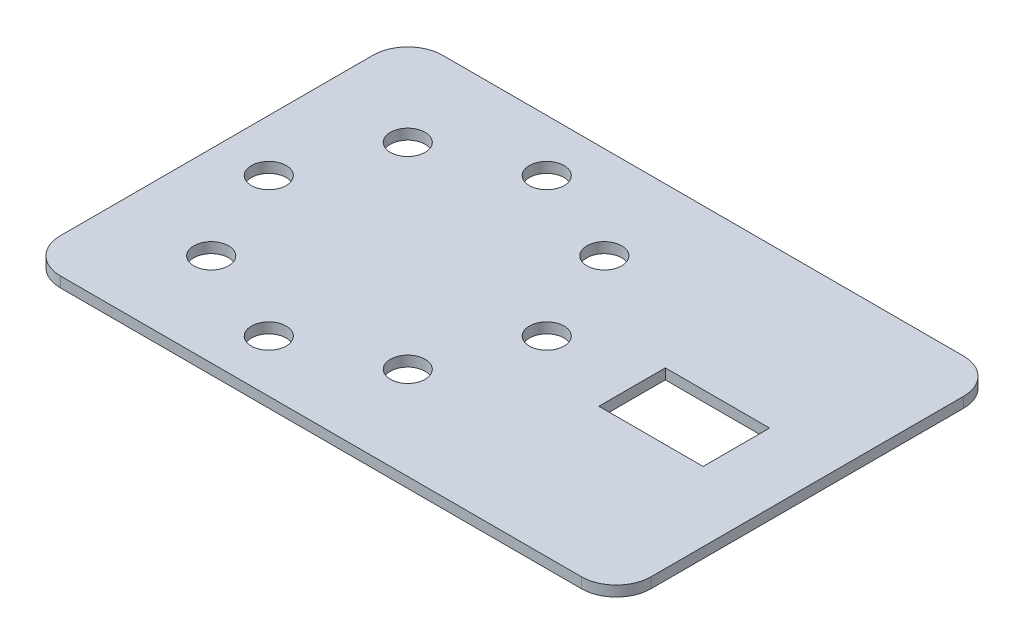
SolidWorks part; units mm, degrees
ref_plane "Front Plane" through (0, 0, 0) normal (0, 0, 1) x (1, 0, 0)
ref_plane "Top Plane" through (0, 0, 0) normal (0, 1, 0) x (1, 0, 0)
ref_plane "Right Plane" through (0, 0, 0) normal (1, 0, 0) x (0, 0, -1)
sketch "Sketch1" plane through (0, 0, 0) normal (0, 1, 0) x (1, 0, 0)
  line L0 (-37.5, 0) -> (-15, 0) construction
  line L1 (42.5, -27.5) -> (-42.5, -27.5)
  line L2 (42.5, -27.5) -> (42.5, 27.5)
  line L3 (42.5, 27.5) -> (-42.5, 27.5)
  line L4 (-42.5, -27.5) -> (-42.5, 27.5)
  line L5 (42.5, -27.5) -> (-42.5, 27.5) construction
  line L6 (42.5, 27.5) -> (-42.5, -27.5) construction
  line L7 (32.5, -5) -> (17.5, -5)
  line L8 (32.5, -5) -> (32.5, 4.5667)
  line L9 (32.5, 4.5667) -> (17.5, 4.5667)
  line L10 (17.5, -5) -> (17.5, 4.5667)
  line L11 (32.5, -5) -> (17.5, 4.5667) construction
  line L12 (32.5, 4.5667) -> (17.5, -5) construction
  circle A0 centre (-35, 0) radius 2.5
  circle A1 centre (-15, 0) radius 22.5
  circle A2 centre (-29.1421, 14.1421) radius 2.5
  circle A3 centre (-15, 20) radius 2.5
  circle A4 centre (-0.8579, 14.1421) radius 2.5
  circle A5 centre (5, 0) radius 2.5
  circle A6 centre (-0.8579, -14.1421) radius 2.5
  circle A7 centre (-15, -20) radius 2.5
  circle A8 centre (-29.1421, -14.1421) radius 2.5
  point P0 (0, 0)
  point P6 (25, -0.2166)
  dimension "D3" = 5
  dimension "D4" = 7.5
  dimension "D1" = 85
  dimension "D2" = 55
  dimension "D5" = 27.5
  dimension "D6" = 22.5
  dimension "D8" = 22.5
  dimension "D9" = 15
  dimension "D10" = 10
  dimension "D7" = 8
extrude "Boss-Extrude1" add sketch "Sketch1" along normal blind 1.5 contours A1 A8 A7 A6 A5 A4 A3 A2 A0 | L4 L1 L2 L3 A1 L7 L10 L9 L8
fillet "Fillet1" radius 5 4 edges at (-42.5, 0.75, -27.5) (-42.5, 0.75, 27.5) (42.5, 0.75, -27.5) (42.5, 0.75, 27.5)
